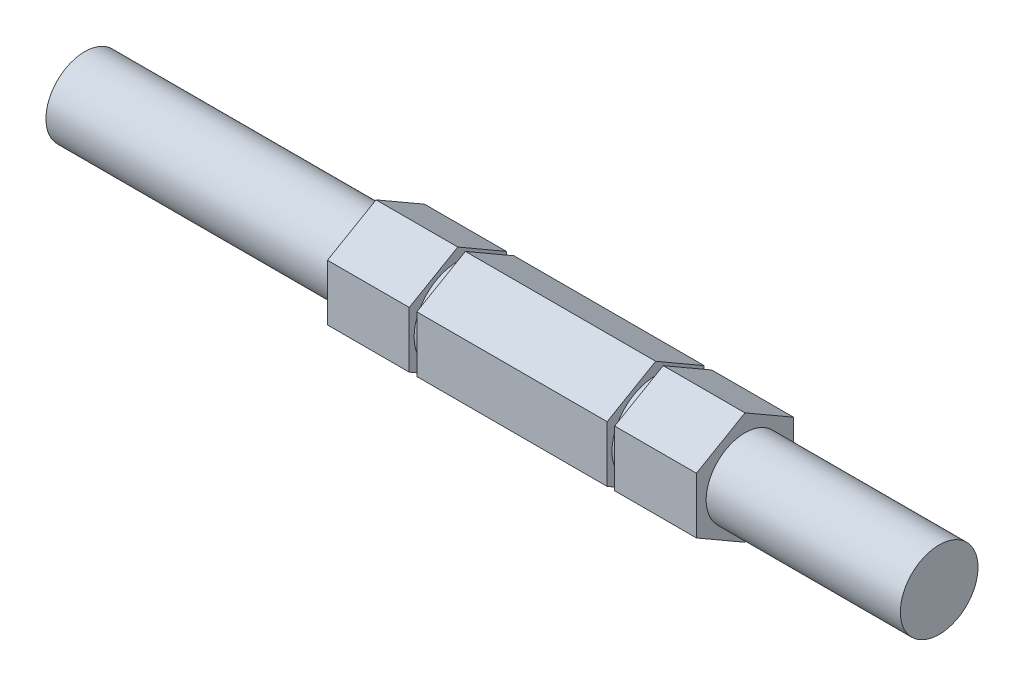
SolidWorks part; units mm, degrees
material "Stainless Steel (ferritic)"
ref_plane "Front Plane" through (0, 0, 0) normal (0, 0, 1) x (1, 0, 0)
ref_plane "Top Plane" through (0, 0, 0) normal (0, 1, 0) x (1, 0, 0)
ref_plane "Right Plane" through (0, 0, 0) normal (1, 0, 0) x (0, 0, -1)
sketch "Sketch1" plane through (0, 0, 0) normal (1, 0, 0) x (0, 0, -1)
  line L1 (0, -7.3323) -> (6.35, -3.6662)
  line L2 (6.35, -3.6662) -> (6.35, 3.6662)
  line L3 (6.35, 3.6662) -> (0, 7.3323)
  line L4 (0, 7.3323) -> (-6.35, 3.6662)
  line L5 (-6.35, 3.6662) -> (-6.35, -3.6662)
  line L6 (-6.35, -3.6662) -> (0, -7.3323)
  circle A0 centre (0, 0) radius 6.35 construction
  dimension "D1" = 12.7
  dimension "D2" = 14.6647
extrude "Boss-Extrude1" add sketch "Sketch1" along normal blind 48.26
sketch "Sketch4" plane through (0, 0, 0) normal (-1, 0, 0) x (0, 0, 1)
  circle A0 centre (0, 0) radius 5.08
extrude "Boss-Extrude2" add sketch "Sketch4" along normal blind 38.1
sketch "Sketch5" plane through (48.26, 0, 0) normal (1, 0, 0) x (0, 0, -1)
  circle A0 centre (0, 0) radius 5.08
extrude "Boss-Extrude3" add sketch "Sketch5" along normal blind 25.4
sketch "Sketch7" plane through (0, 0, 0) normal (0, 0, 1) x (1, 0, 0)
  line L0 (-57.5946, 0) -> (82.9867, 0) construction
sketch "Sketch3" plane through (0, 0, 0) normal (0, 1, 0) x (1, 0, 0)
  line L0 (24.13, 0) -> (24.13, 19.8712) construction
  line L1 (48.26, 0) -> (0, 0) construction
  line L2 (48.26, 6.35) -> (0, 6.35) construction
  line L3 (37.5666, 7.9338) -> (37.5666, 5.715)
  line L4 (36.576, 7.9338) -> (37.5666, 7.9338)
  line L5 (10.6934, 5.715) -> (11.684, 5.715)
  line L6 (11.684, 5.715) -> (11.684, 7.9338)
  line L7 (11.684, 7.9338) -> (10.6934, 7.9338)
  line L8 (10.6934, 7.9338) -> (10.6934, 5.715)
  line L9 (24.13, 0) -> (-54.0901, 0) construction
  line L10 (36.576, 5.715) -> (36.576, 7.9338)
  line L11 (37.5666, 5.715) -> (36.576, 5.715)
  point P4 (10.6934, 5.715)
  dimension "D1" = 12.446
  dimension "D2" = 0.635
  dimension "D3" = 0.9906
revolve "Cut-Revolve2" cut sketch "Sketch3" angle 360 about L0
equation "\"asdf\"=0.484"
